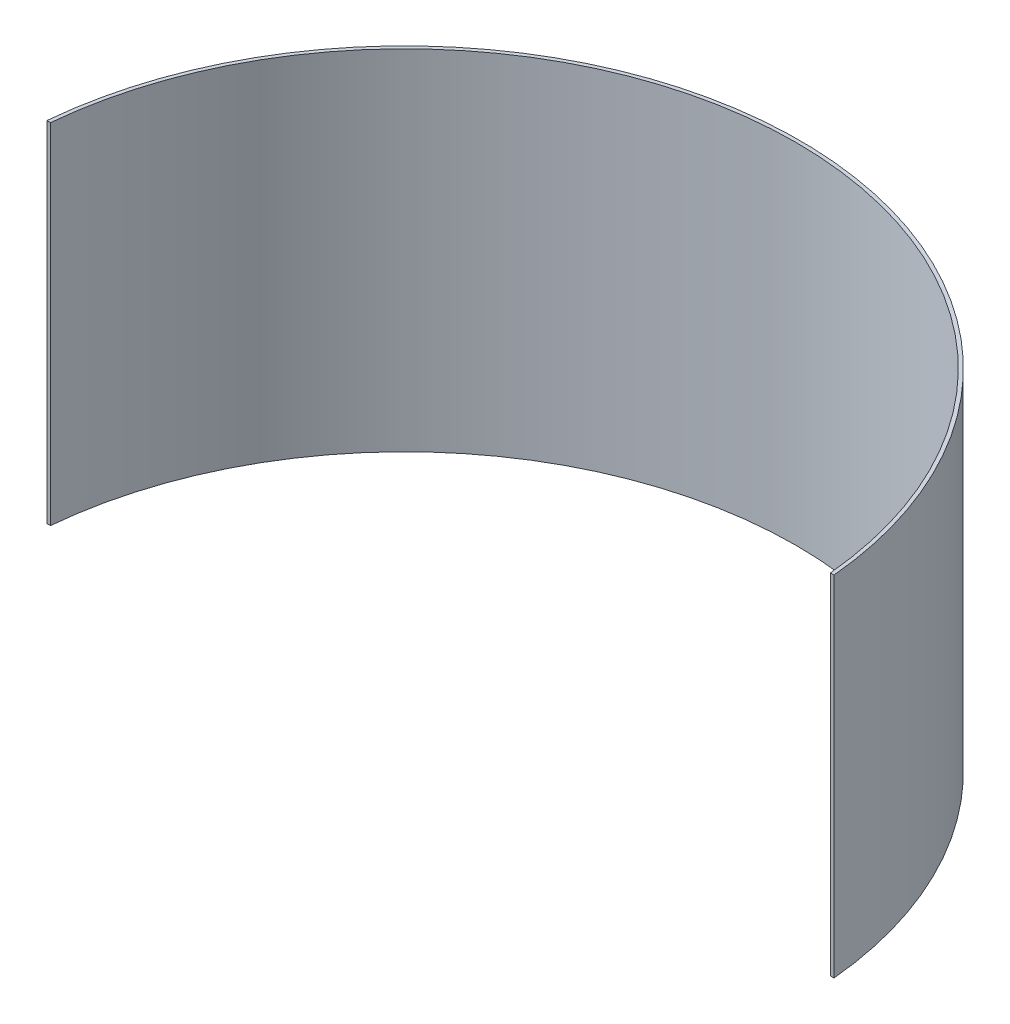
SolidWorks part; units mm, degrees
ref_plane "Front Plane" through (0, 0, 0) normal (0, 0, 1) x (1, 0, 0)
ref_plane "Top Plane" through (0, 0, 0) normal (0, 1, 0) x (1, 0, 0)
ref_plane "Right Plane" through (0, 0, 0) normal (1, 0, 0) x (0, 0, -1)
sketch "Sketch1" plane through (0, 0, 0) normal (0, 1, 0) x (1, 0, 0)
  line L0 (0, 0) -> (10.042, 0)
  line L1 (2190.89, 0) -> (2180.848, 0)
  arc A0 (0, 0) -> (2190.89, 0) centre (1095.445, -100.0013) cw
  arc A1 (10.042, 0) -> (2180.848, 0) centre (1095.445, -100.0013) cw
  arc A2 (9.9586, -0.9091) -> (2180.9314, -0.9091) centre (1095.445, -100.0013) cw construction
  dimension "D2" = 1100
  dimension "D1" = 2190.89
  dimension "D3" = 10
extrude "Boss-Extrude1" add sketch "Sketch1" along normal blind 971.31
